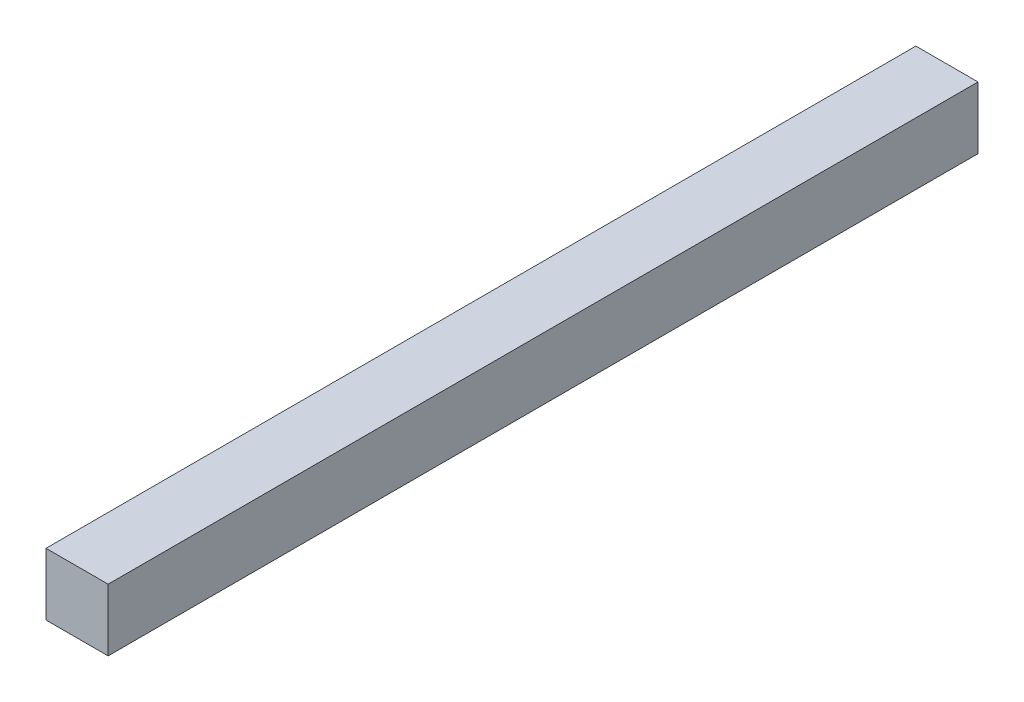
SolidWorks part; units mm, degrees
ref_plane "Front Plane" through (0, 0, 0) normal (0, 0, 1) x (1, 0, 0)
ref_plane "Top Plane" through (0, 0, 0) normal (0, 1, 0) x (1, 0, 0)
ref_plane "Right Plane" through (0, 0, 0) normal (1, 0, 0) x (0, 0, -1)
sketch "Sketch1" plane through (0, 0, 0) normal (0, 0, 1) x (1, 0, 0)
  line L1 (0, 0) -> (9.525, 0)
  line L2 (0, 0) -> (0, 9.525)
  line L3 (0, 9.525) -> (9.525, 9.525)
  line L4 (9.525, 0) -> (9.525, 9.525)
  dimension "D1" = 9.525
  dimension "D2" = 9.525
extrude "Boss-Extrude1" add sketch "Sketch1" along normal blind 133.35
